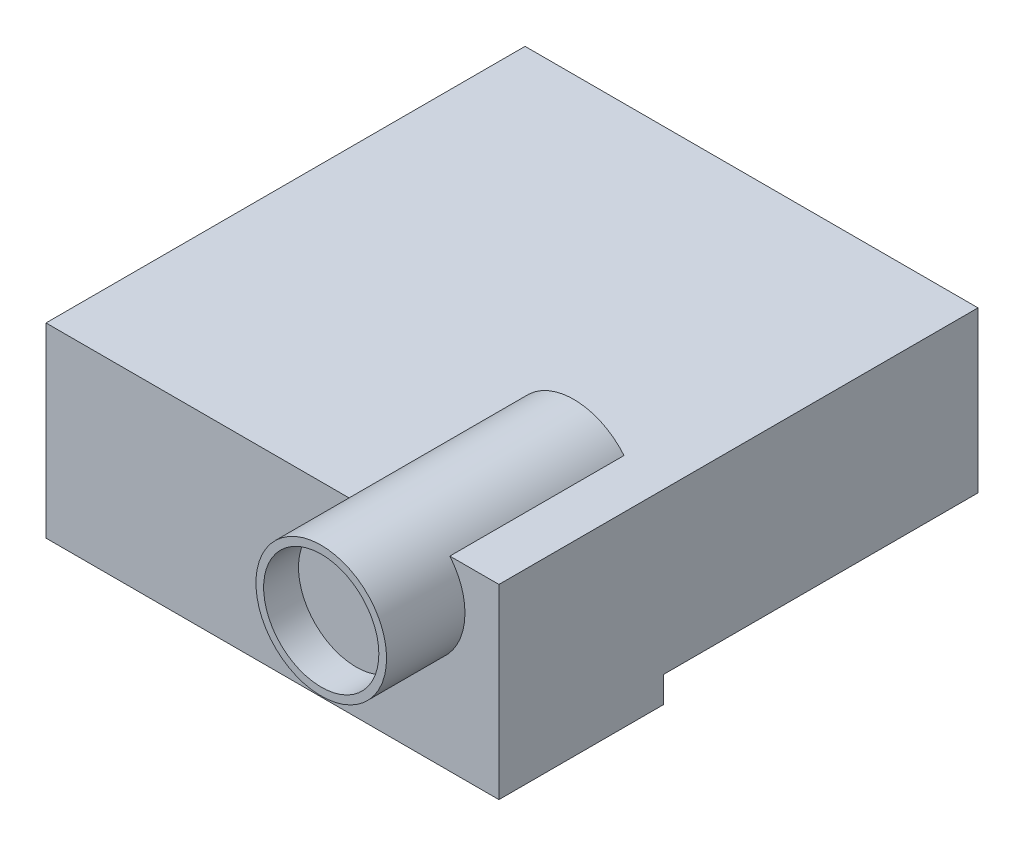
SolidWorks part; units mm, degrees
ref_plane "정면" through (0, 0, 0) normal (0, 0, 1) x (1, 0, 0)
ref_plane "윗면" through (0, 0, 0) normal (0, 1, 0) x (1, 0, 0)
ref_plane "우측면" through (0, 0, 0) normal (1, 0, 0) x (0, 0, -1)
sketch "스케치1" plane through (0, 0, 0) normal (0, 1, 0) x (1, 0, 0)
  line L1 (0, 0) -> (260, 0)
  line L2 (0, 0) -> (0, 275)
  line L3 (0, 275) -> (260, 275)
  line L4 (260, 0) -> (260, 275)
  dimension "D1" = 260
  dimension "D2" = 275
extrude "보스-돌출1" add sketch "스케치1" along normal blind 107
sketch "스케치2" plane through (0, 0, 0) normal (0, 0, 1) x (1, 0, 0)
  line L0 (260, 107) -> (260, 0) construction
  line L2 (0, 0) -> (260, 0) construction
  circle A0 centre (203, 83) radius 37.5
  dimension "D2" = 75
  dimension "D1" = 57
  dimension "D3" = 83
extrude "보스-돌출2" add sketch "스케치2" along normal blind 25 and the other way blind 100
sketch "스케치3" plane through (260, 0, 0) normal (1, 0, 0) x (0, 0, -1)
  line L0 (275, 107) -> (275, 0) construction
  line L1 (275, 15) -> (94.4841, 15)
  line L2 (275, 15) -> (275, 0)
  line L3 (275, 0) -> (94.4841, 0)
  line L4 (94.4841, 15) -> (94.4841, 0)
  line L5 (0, 0) -> (275, 0) construction
  dimension "D1" = 15
extrude "컷-돌출1" cut sketch "스케치3" against normal through all
hole_wizard "M4x0.7 나사 구멍1" positions "스케치5" profile "스케치4" tap size "M4x0.7" standard "Ansi Metric"
sketch "스케치5" plane through (0, 15, 0) normal (0, -1, 0) x (-1, 0, 0)
  line L0 (0, 235) -> (-36, 235) construction
  line L1 (0, 275) -> (0, 94.4841) construction
  line L2 (-36, 235) -> (-209, 235) construction
  line L3 (-209, 235) -> (-260, 235) construction
  line L4 (-260, 275) -> (-260, 94.4841) construction
  line L6 (0, 275) -> (-260, 275) construction
  point P0 (-36, 235)
  point P2 (-209, 235)
  dimension "D1" = 173
  dimension "D2" = 40
  dimension "D3" = 36
sketch "스케치4" plane through (36, 15, -235) normal (1, 0, 0) x (0, 0, -1)
  line L0 (0, 0) -> (0, 12.4914)
  line L1 (0, 12.4914) -> (1.65, 11.5)
  line L2 (1.65, 11.5) -> (1.65, 0)
  line L5 (1.65, 0) -> (0, 0)
  line L10 (0, 12.4914) -> (-1.65, 11.5) construction
  line L11 (0, -6.35) -> (0, 107.95) construction
  dimension "탭 드릴 지름" = 3.3
  dimension "탭 드릴 깊이" = 11.5
  dimension "드릴 각도" = 118
cosmetic thread "구멍 나사산1" parameters "D1"=8, "D2"=4
cosmetic thread "구멍 나사산2" parameters "D1"=8, "D2"=4
ref_plane "평면1" through (203, 0, 0) normal (1, 0, 0) x (0, 0, -1)
sketch "스케치17" plane through (0, 0, 25) normal (0, 0, 1) x (1, 0, 0)
  circle A0 centre (203, 83) radius 37.5
  circle A1 centre (203, 83) radius 33.0674
extrude "보스-돌출4" add sketch "스케치17" along normal blind 20
ref_plane "평면6" through (0, 0, 135) normal (0, 0, 1) x (1, 0, 0)
sketch "화면1" plane through (203, 0, 0) normal (1, 0, 0) x (0, 0, -1)
  line L4 (0, 0) -> (94.4841, 0) construction
  line L5 (-80, 130) -> (-80, 90) construction
  line L8 (-45, 120.5) -> (-45, 45.5) construction
  line L14 (-135, 161) -> (-135, 96) construction
  line L16 (-135, 161) -> (-80, 130) construction
  line L17 (-80, 130) -> (-22.829, 97.7763) construction
  line L18 (-135, 96) -> (-80, 90) construction
  line L19 (-80, 90) -> (-22.829, 83.7632) construction
  line L20 (-22.829, 83.7632) -> (-22.829, 97.7763) construction
  dimension "D1" = 40
  dimension "D2" = 35
  dimension "D3" = 90
  dimension "D4" = 65
  dimension "D5" = 90
  dimension "D6" = 96
sketch "화면2" plane through (0, 0, 135) normal (0, 0, 1) x (1, 0, 0)
  line L1 (247, 96) -> (159, 96)
  line L2 (247, 96) -> (247, 161)
  line L3 (247, 161) -> (159, 161)
  line L4 (159, 96) -> (159, 161)
  line L5 (247, 96) -> (159, 161) construction
  line L6 (247, 161) -> (159, 96) construction
  point P0 (203, 128.5)
  point P5 (203, 161)
  dimension "D1" = 88
  dimension "D2" = 65
ref_plane "평면7" through (0, 0, 12.5) normal (0, 0, 1) x (1, 0, 0)
sketch "스케치18" plane through (0, 0, 0) normal (0, -1, 0) x (1, 0, 0)
  line L0 (209, -235) -> (143.9335, -49.0555) construction
  line L1 (143.9335, -49.0555) -> (36, -235) construction
  dimension "D1" = 197
  dimension "D2" = 215
hole_wizard "M4 여유 구멍1" positions "스케치20" profile "스케치19" hole size "M4" standard "Ansi Metric"
sketch "스케치20" plane through (0, 0, 0) normal (0, -1, 0) x (-1, 0, 0)
  point P0 (-143.9335, 49.0555)
sketch "스케치19" plane through (143.9335, 0, -49.0555) normal (1, 0, 0) x (0, 0, -1)
  line L0 (0, 0) -> (0, 21.3519)
  line L1 (0, 21.3519) -> (2.25, 20)
  line L2 (2.25, 20) -> (2.25, 0)
  line L5 (2.25, 0) -> (0, 0)
  line L10 (0, 21.3519) -> (-2.25, 20) construction
  line L11 (0, -6.35) -> (0, 107.95) construction
  dimension "구멍 지름" = 4.5
  dimension "구멍 깊이" = 20
  dimension "드릴 각도" = 118
